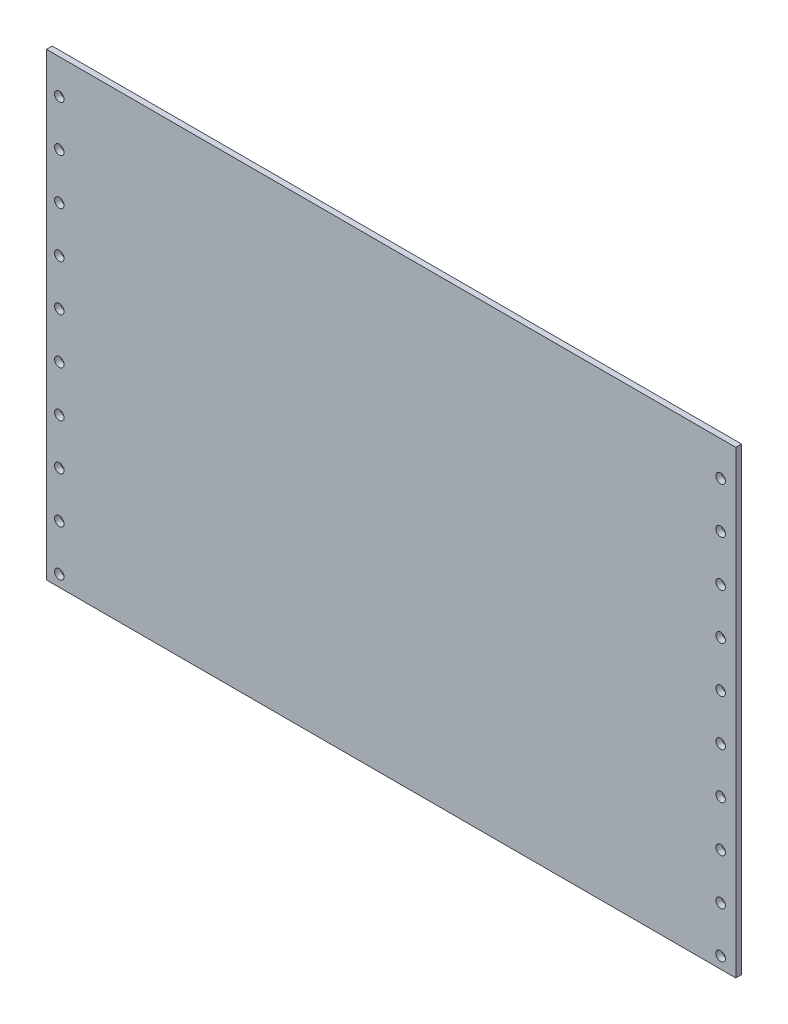
SolidWorks part; units mm, degrees
material "6061-T6 (SS)"
ref_plane "Front Plane" through (0, 0, 0) normal (0, 0, 1) x (1, 0, 0)
ref_plane "Top Plane" through (0, 0, 0) normal (0, 1, 0) x (1, 0, 0)
ref_plane "Right Plane" through (0, 0, 0) normal (1, 0, 0) x (0, 0, -1)
sketch "Sketch1" plane through (0, 0, 0) normal (0, 0, 1) x (1, 0, 0)
  line L1 (-190.5, -127) -> (190.5, -127)
  line L2 (-190.5, -127) -> (-190.5, 127)
  line L3 (-190.5, 127) -> (190.5, 127)
  line L4 (190.5, -127) -> (190.5, 127)
  line L5 (-190.5, -127) -> (190.5, 127) construction
  line L6 (-190.5, 127) -> (190.5, -127) construction
  point P0 (0, 0)
  dimension "D1" = 381
  dimension "D2" = 254
extrude "Boss-Extrude1" add sketch "Sketch1" along normal blind 3.175
sketch "Sketch2" plane through (0, 0, 3.175) normal (0, 0, 1) x (1, 0, 0)
  line L0 (-190.5, 127) -> (-190.5, -127) construction
  line L1 (190.5, 127) -> (-190.5, 127) construction
  point P0 (-183.388, 107.95)
  point P6 (182.118, 107.95)
  point P8 (182.118, 82.55)
  point P9 (182.118, 57.15)
  point P10 (182.118, 31.75)
  point P11 (182.118, 6.35)
  point P12 (182.118, -19.05)
  point P13 (182.118, -44.45)
  point P14 (182.118, -69.85)
  point P15 (182.118, -95.25)
  point P16 (182.118, -120.65)
  point P17 (-183.388, 82.55)
  point P18 (-183.388, 57.15)
  point P19 (-183.388, 31.75)
  point P20 (-183.388, 6.35)
  point P21 (-183.388, -19.05)
  point P22 (-183.388, -44.45)
  point P23 (-183.388, -69.85)
  point P24 (-183.388, -95.25)
  point P25 (-183.388, -120.65)
  dimension "D1" = 7.112
  dimension "D2" = 19.05
  dimension "D5" = 365.506
  dimension "D3" = 2
  dimension "D4" = 10
hole_wizard "#5 (0.2055) Diameter Hole1" positions "Sketch3" profile "Sketch4" hole size "#5" standard "ANSI Inch" end condition through all
sketch "Sketch3" plane through (0, 0, 3.175) normal (0, 0, 1) x (1, 0, 0)
  point P0 (-183.388, 107.95)
  point P3 (-183.388, 82.55)
  point P6 (-183.388, 57.15)
  point P9 (-183.388, 31.75)
  point P12 (-183.388, 6.35)
  point P15 (-183.388, -19.05)
  point P18 (-183.388, -44.45)
  point P21 (-183.388, -69.85)
  point P24 (-183.388, -120.65)
  point P27 (-183.388, -95.25)
  point P30 (182.118, -120.65)
  point P33 (182.118, -95.25)
  point P36 (182.118, -69.85)
  point P39 (182.118, -44.45)
  point P42 (182.118, -19.05)
  point P45 (182.118, 6.35)
  point P48 (182.118, 31.75)
  point P51 (182.118, 57.15)
  point P54 (182.118, 82.55)
  point P57 (182.118, 107.95)
sketch "Sketch4" plane through (-183.388, 107.95, 3.175) normal (1, 0, 0) x (0, -1, 0)
  line L0 (0, 0) -> (0, 3.175)
  line L1 (0, 3.175) -> (2.6098, 3.175)
  line L2 (2.6098, 3.175) -> (2.6098, 0)
  line L5 (2.6098, 0) -> (0, 0)
  line L11 (0, -6.35) -> (0, 107.95) construction
  dimension "Thru Hole Dia." = 5.2197
  dimension "Thru Hole Depth" = 3.175
